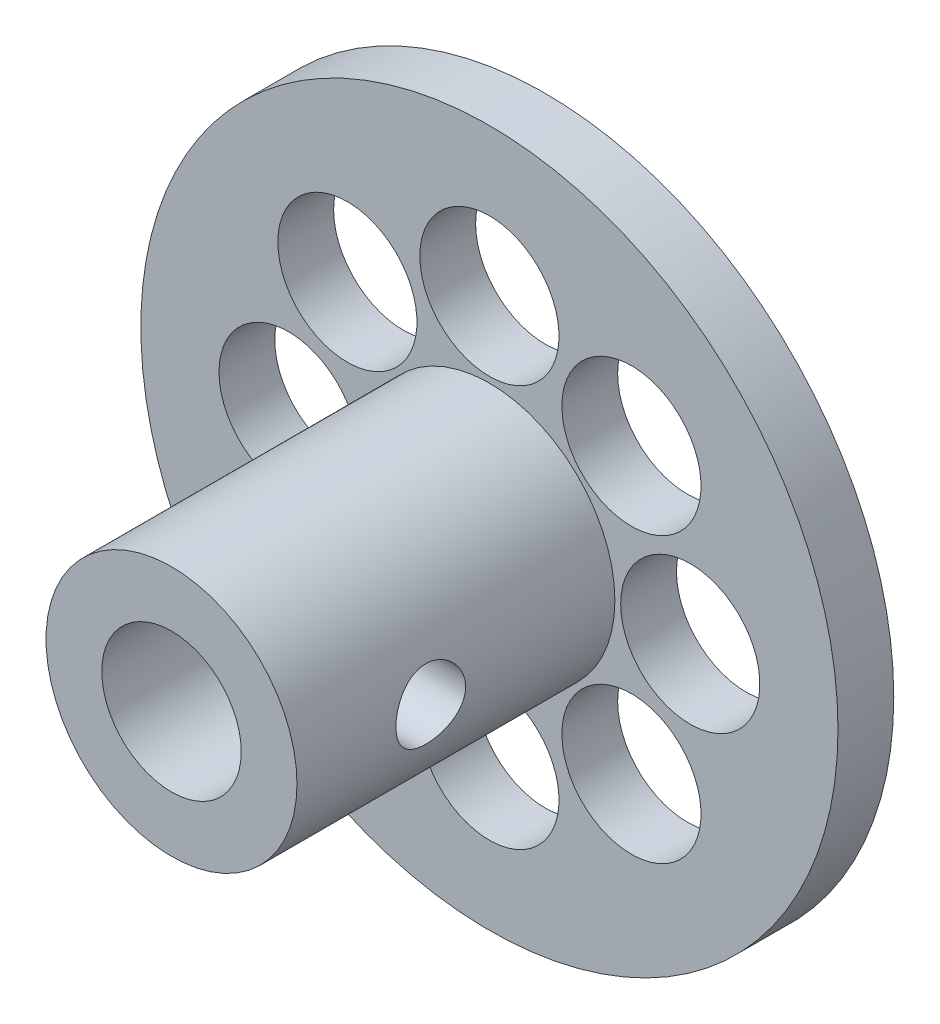
SolidWorks part; units mm, degrees
ref_plane "Front Plane" through (0, 0, 0) normal (0, 0, 1) x (1, 0, 0)
ref_plane "Top Plane" through (0, 0, 0) normal (0, 1, 0) x (1, 0, 0)
ref_plane "Right Plane" through (0, 0, 0) normal (1, 0, 0) x (0, 0, -1)
sketch "Sketch1" plane through (0, 0, 0) normal (0, 0, 1) x (1, 0, 0)
  circle A0 centre (0, 0) radius 31.75
  dimension "D1" = 63.5
extrude "Boss-Extrude1" add sketch "Sketch1" along normal blind 5.08 contours A0
sketch "Sketch2" plane through (0, 0, 0) normal (0, 0, -1) x (-1, 0, 0)
  circle A0 centre (0, 0) radius 6.35
  circle A1 centre (0, 0) radius 31.75 construction
  dimension "D1" = 12.7
extrude "Cut-Extrude1" cut sketch "Sketch2" against normal blind 5.08
sketch "Sketch3" plane through (0, 0, 5.08) normal (0, 0, 1) x (1, 0, 0)
  circle A0 centre (0, 0) radius 11.43
  circle A1 centre (0, 0) radius 15.996
  circle A2 centre (0, 0) radius 6.35 construction
  dimension "D1" = 31.9921
  dimension "D2" = 22.86
extrude "Boss-Extrude2" add sketch "Sketch3" along normal blind 28.956 contours A0
sketch "Sketch5" plane through (0, 0, 34.036) normal (0, 0, 1) x (1, 0, 0)
  circle A0 centre (0, 0) radius 6.35
  circle A1 centre (0, 0) radius 11.43 construction
  dimension "D1" = 12.7
extrude "Cut-Extrude2" cut sketch "Sketch5" against normal blind 29.21 contours A0
sketch "Sketch6" plane through (0, 0, 0) normal (0, 0, -1) x (-1, 0, 0)
  circle A0 centre (0, 18.2944) radius 6.3371
  circle A2 centre (12.9361, 12.9361) radius 6.3371
  circle A3 centre (18.2944, 0) radius 6.3371
  circle A4 centre (12.9361, -12.9361) radius 6.3371
  circle A5 centre (0, -18.2944) radius 6.3371
  circle A6 centre (-12.9361, -12.9361) radius 6.3371
  circle A7 centre (-18.2944, 0) radius 6.3371
  circle A8 centre (-12.9361, 12.9361) radius 6.3371
  circle A9 centre (0, 0) radius 6.35 construction
  point P21 (0, 0)
  dimension "D1" = 12.6742
  dimension "D2" = 8
  dimension "D3" = 12.9361
extrude "Cut-Extrude3" cut sketch "Sketch6" against normal blind 5.08
sketch "Sketch7" plane through (0, 0, 0) normal (1, 0, 0) x (0, 0, -1)
  circle A0 centre (-21.8513, 0) radius 3.175
  dimension "D1" = 6.35
  dimension "D2" = 21.8513
extrude "Cut-Extrude4" cut sketch "Sketch7" against normal blind 11.938 and the other way blind 17.526 contours A0
